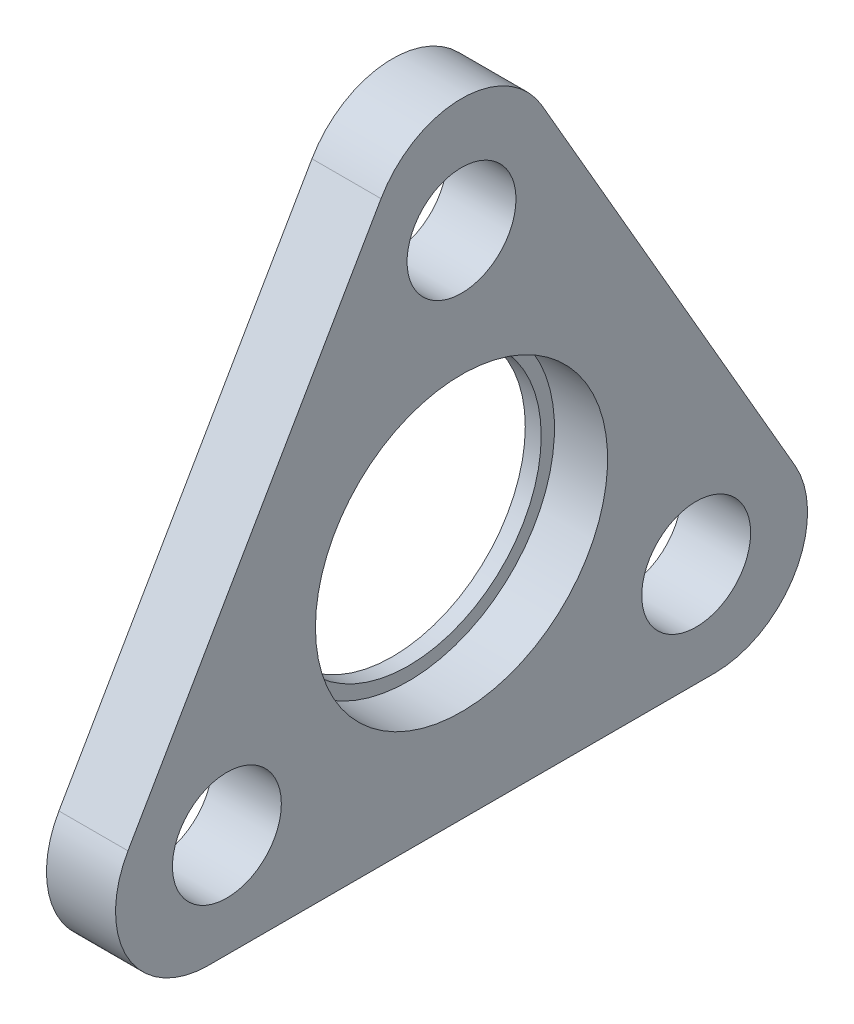
SolidWorks part; units mm, degrees
ref_plane "前视基准面" through (0, 0, 0) normal (0, 0, 1) x (1, 0, 0)
ref_plane "上视基准面" through (0, 0, 0) normal (0, 1, 0) x (1, 0, 0)
ref_plane "右视基准面" through (0, 0, 0) normal (1, 0, 0) x (0, 0, -1)
other "Configuration Table"
sketch "草图1" plane through (0, 0, 0) normal (1, 0, 0) x (0, 0, -1)
  line L0 (0, 0) -> (0, 10.2) construction
  line L1 (0, 0) -> (8.8335, -5.1) construction
  line L2 (0, 0) -> (-8.8335, -5.1) construction
  line L3 (0, 0) -> (0, 18)
  line L4 (0, 0) -> (15.5885, -9)
  line L5 (0, 0) -> (-15.5885, -9)
  line L6 (0, 18) -> (-15.5885, -9)
  line L7 (-15.5885, -9) -> (15.5885, -9)
  line L8 (15.5885, -9) -> (0, 18)
  circle A0 centre (0, 10.2) radius 3.55 construction
  circle A1 centre (8.8335, -5.1) radius 3.55 construction
  circle A2 centre (-8.8335, -5.1) radius 3.55 construction
  circle A3 centre (0, 10.2) radius 2.05
  circle A4 centre (8.8335, -5.1) radius 2.05
  circle A5 centre (-8.8335, -5.1) radius 2.05
  point P7 (0, 0)
  point P19 (0, 0)
  dimension "D3" = 7.1
  dimension "D4" = 7.1
  dimension "D5" = 7.1
  dimension "D11" = 4.1
  dimension "D1" = 10.2
  dimension "D6" = 120
  dimension "D7" = 120
  dimension "D8" = 18
  dimension "D9" = 18
  dimension "D10" = 18
  dimension "D2" = 3
  dimension "D12" = 3
extrude "凸台-拉伸2" add sketch "草图1" along normal blind 2.6 contours A4 L4 L8 L3 A3 | A5 L5 L3 A3 L6 | A5 L5 L7 L4 A4
fillet "圆角1" radius 3.5 3 edges at (1.3, -9, 15.5885) (1.3, -9, -15.5885) (1.3, 18, 0)
sketch "草图4" plane through (0, 0, 0) normal (-1, 0, 0) x (0, 0, 1)
  circle A0 centre (0, 0) radius 5.5
extrude "切除-拉伸1" cut sketch "草图4" against normal through all
sketch "草图6" plane through (0, 0, 0) normal (-1, 0, 0) x (0, 0, 1)
  circle A0 centre (0, 0) radius 5
  circle A1 centre (0, 0) radius 5.5
extrude "凸台-拉伸4" add sketch "草图6" against normal blind 0.6 separate body
